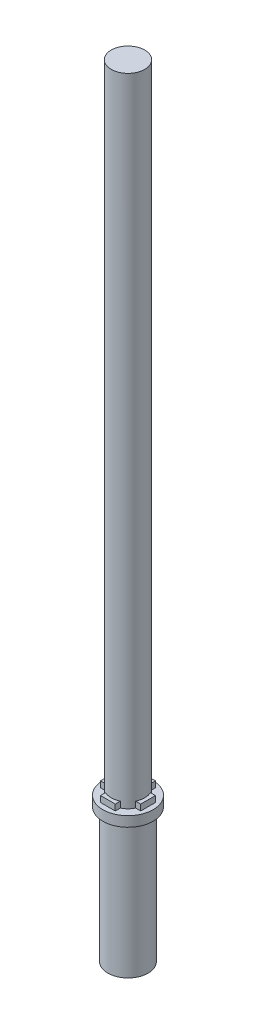
SolidWorks part; units mm, degrees
ref_plane "前视基准面" through (0, 0, 0) normal (0, 0, 1) x (1, 0, 0)
ref_plane "上视基准面" through (0, 0, 0) normal (0, 1, 0) x (1, 0, 0)
ref_plane "右视基准面" through (0, 0, 0) normal (1, 0, 0) x (0, 0, -1)
sketch "草图1" plane through (0, 0, 0) normal (0, 1, 0) x (1, 0, 0)
  circle A0 centre (0, 0) radius 5.25
  circle A1 centre (0, 0) radius 6
  dimension "D1" = 10.5
  dimension "D2" = 12
extrude "凸台-拉伸2" add sketch "草图1" along normal blind 40 contours A1 | A0
sketch "草图2" plane through (0, 40, 0) normal (0, 1, 0) x (1, 0, 0)
  circle A0 centre (0, 0) radius 7.5
  dimension "D1" = 15
extrude "凸台-拉伸3" add sketch "草图2" along normal blind 3
sketch "草图3" plane through (0, 43, 0) normal (0, 1, 0) x (1, 0, 0)
  circle A0 centre (0, 0) radius 5
  dimension "D1" = 10
extrude "凸台-拉伸4" add sketch "草图3" along normal blind 190
sketch "草图4" plane through (0, 43, 0) normal (0, 1, 0) x (1, 0, 0)
  line L0 (0, 0) -> (5, 0) construction
  line L1 (0, 0) -> (0, 5) construction
  line L3 (0, 0) -> (6, 0) construction
  line L4 (0, -2.2) -> (0, 2.2)
  line L8 (-2.2, 2.2) -> (-2.2, 6)
  line L13 (-2.2, 6) -> (2.2, 6)
  line L14 (2.2, 6) -> (2.2, 2.2)
  line L15 (2.2, 2.2) -> (6, 2.2)
  line L16 (6, 2.2) -> (6, -2.2)
  line L17 (6, -2.2) -> (2.2, -2.2)
  line L18 (2.2, -2.2) -> (2.2, -6)
  line L19 (2.2, -6) -> (-2.2, -6)
  line L20 (-2.2, -6) -> (-2.2, -2.2)
  line L21 (-2.2, -2.2) -> (-6, -2.2)
  line L22 (-6, -2.2) -> (-6, 2.2)
  line L23 (-6, 2.2) -> (-2.2, 2.2)
  circle M7 centre (0, 0) radius 5
  dimension "D1" = 2.2
  dimension "D2" = 2.2
  dimension "D3" = 2.2
  dimension "D4" = 2.2
  dimension "D5" = 2.2
  dimension "D6" = 2.2
  dimension "D7" = 2.2
  dimension "D8" = 2.2
  dimension "D9" = 6
  dimension "D10" = 6
  dimension "D11" = 6
  dimension "D12" = 6
extrude "凸台-拉伸6" add sketch "草图4" along normal blind 1.8 contours L17 L16 L15 M7 | L20 L19 L18 M7 | L14 L13 L8 M7 | L23 L22 L21 M7
